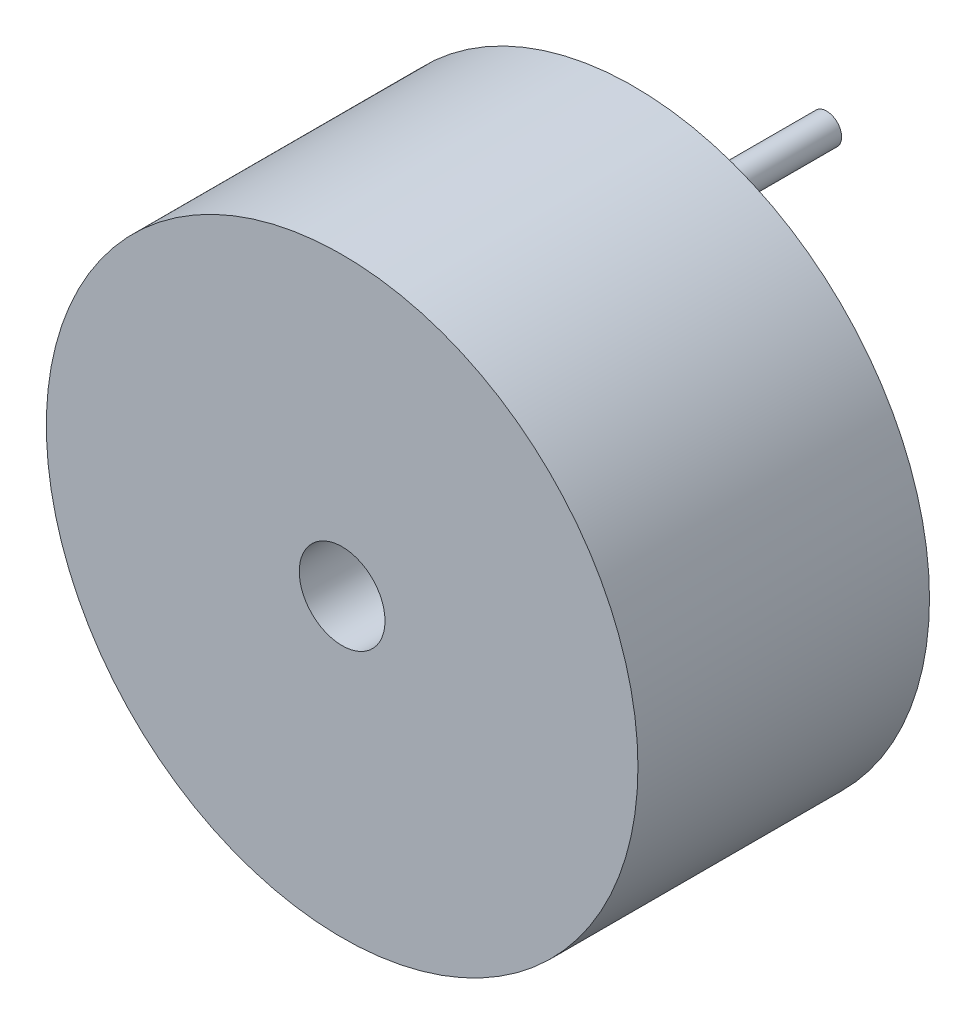
SolidWorks part; units mm, degrees
other "Детальный элемент1"
ref_plane "Спереди" through (0, 0, 0) normal (0, 0, 1) x (1, 0, 0)
ref_plane "Сверху" through (0, 0, 0) normal (0, 1, 0) x (1, 0, 0)
ref_plane "Справа" through (0, 0, 0) normal (1, 0, 0) x (0, 0, -1)
sketch "Эскиз1" plane through (0, 0, 0) normal (0, 0, 1) x (1, 0, 0)
  circle A0 centre (0, 0) radius 6.9
  dimension "D1" = 13.8
extrude "Бобышка-Вытянуть1" add sketch "Эскиз1" along normal blind 6.8
sketch "Эскиз2" plane through (0, 0, 0) normal (0, 0, -1) x (-1, 0, 0)
  circle A0 centre (0, 3.8) radius 0.35
  circle A1 centre (0, -3.8) radius 0.35
  point P4 (0, 0)
  dimension "D3" = 0.7
  dimension "D1" = 3.8
  dimension "D2" = 3.8
extrude "Бобышка-Вытянуть2" add sketch "Эскиз2" along normal blind 4.5
sketch "Эскиз3" plane through (0, 0, 6.8) normal (0, 0, 1) x (1, 0, 0)
  circle A0 centre (0, 0) radius 1
  dimension "D1" = 2
extrude "Вырез-Вытянуть1" cut sketch "Эскиз3" against normal blind 4.5
